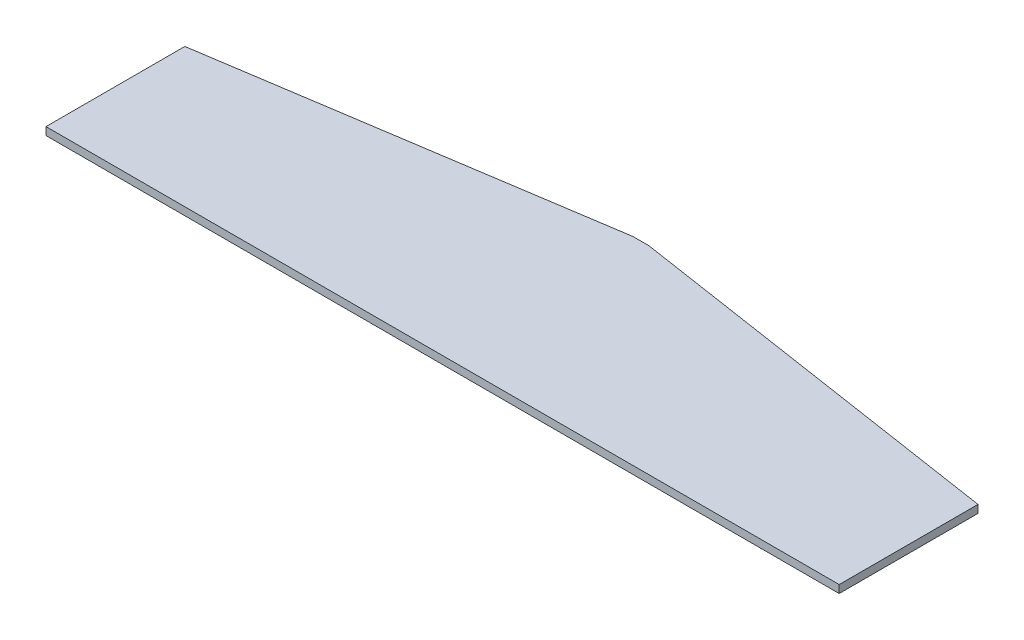
SolidWorks part; units mm, degrees
ref_plane "Front Plane" through (0, 0, 0) normal (0, 0, 1) x (1, 0, 0)
ref_plane "Top Plane" through (0, 0, 0) normal (0, 1, 0) x (1, 0, 0)
ref_plane "Right Plane" through (0, 0, 0) normal (1, 0, 0) x (0, 0, -1)
sketch "Sketch1" plane through (0, 0, 0) normal (0, 1, 0) x (1, 0, 0)
  line L0 (0, 0) -> (10.16, 0)
  line L1 (10.16, 0) -> (259.08, -38.1)
  line L2 (259.08, -38.1) -> (259.08, -127)
  line L3 (259.08, -127) -> (-248.92, -127)
  line L4 (-248.92, -127) -> (-248.92, -38.1)
  line L5 (-248.92, -38.1) -> (0, 0)
  point P5 (0, 0)
  point P8 (0, 0)
  point P9 (5.08, 0)
  dimension "D1" = 508
  dimension "D2" = 254
  dimension "D3" = 10.16
  dimension "D4" = 88.9
  dimension "D5" = 88.9
  dimension "D6" = 127
extrude "Boss-Extrude1" add sketch "Sketch1" along normal blind 5
